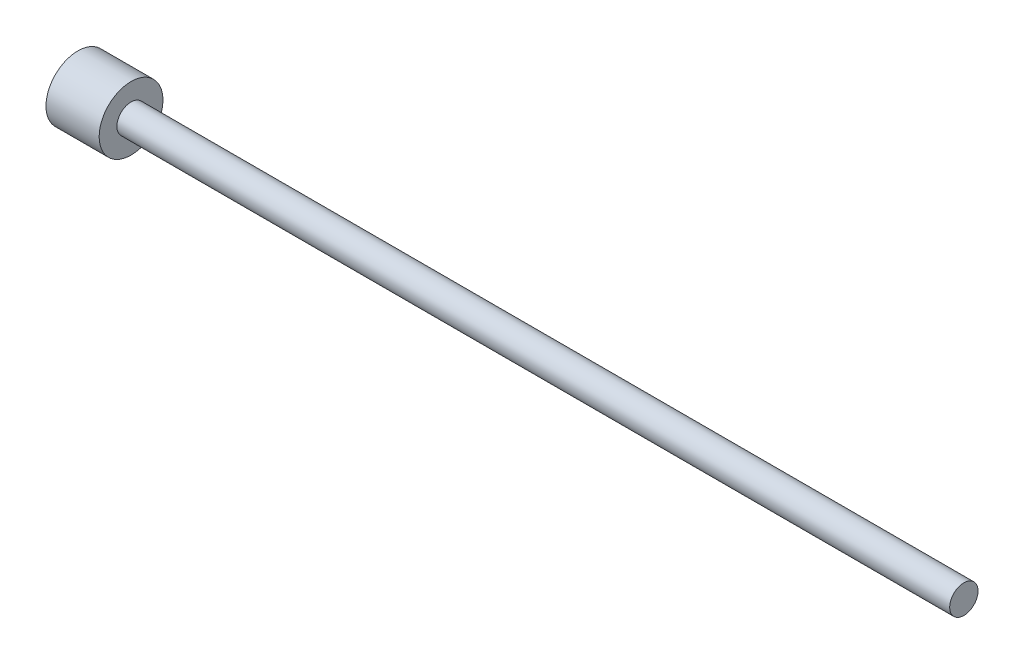
SolidWorks part; units mm, degrees
ref_plane "前视基准面" through (0, 0, 0) normal (0, 0, 1) x (1, 0, 0)
ref_plane "上视基准面" through (0, 0, 0) normal (0, 1, 0) x (1, 0, 0)
ref_plane "右视基准面" through (0, 0, 0) normal (1, 0, 0) x (0, 0, -1)
sketch "草图1" plane through (0, 0, 0) normal (0, 0, 1) x (1, 0, 0)
  line L0 (0, 0) -> (250, 0) construction
  line L1 (0, 0) -> (0, 9)
  line L2 (0, 9) -> (15, 9)
  line L3 (15, 9) -> (15, 4)
  line L4 (15, 4) -> (250, 4)
  line L5 (250, 4) -> (250, 0)
  line L6 (0, 0) -> (250, 0)
  dimension "D1" = 9
  dimension "D2" = 8
  dimension "D3" = 15
  dimension "D4" = 250
revolve "旋转1" add sketch "草图1" angle 360 about L0
